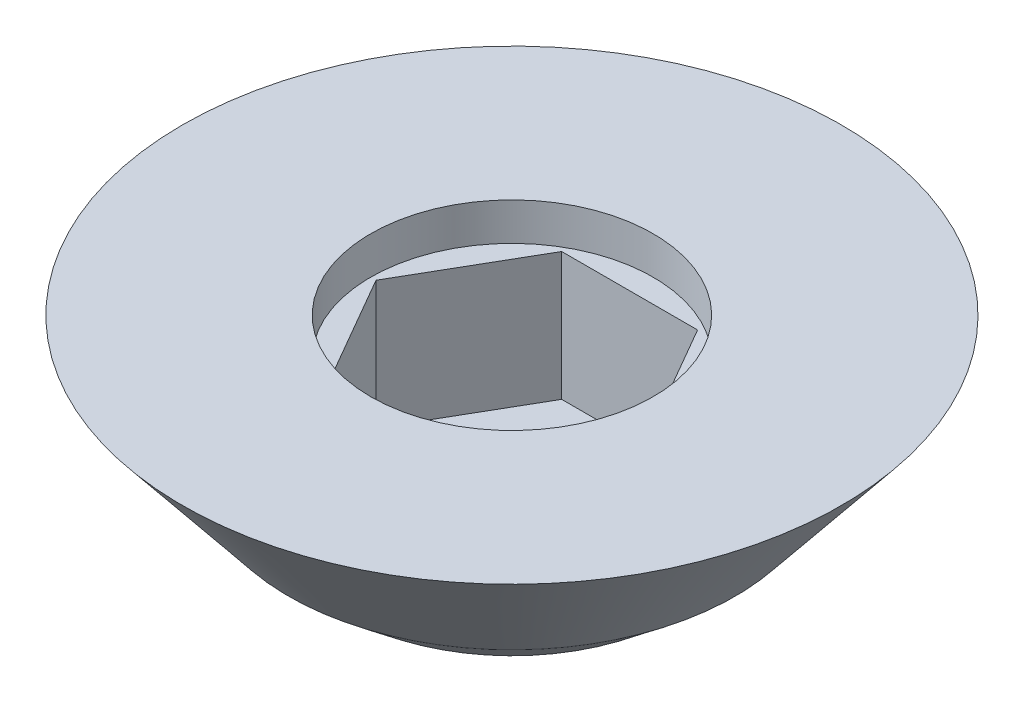
SolidWorks part; units mm, degrees
material "ABS"
ref_plane "Piano frontale" through (0, 0, 0) normal (0, 0, 1) x (1, 0, 0)
ref_plane "Piano superiore" through (0, 0, 0) normal (0, 1, 0) x (1, 0, 0)
ref_plane "Piano destro" through (0, 0, 0) normal (1, 0, 0) x (0, 0, -1)
sketch "Schizzo3" plane through (0, 0, 0) normal (0, 0, 1) x (1, 0, 0)
  line L0 (0, 0) -> (-10, 0) construction
  line L1 (-10, 0) -> (-17.5, 9.3) construction
  line L2 (-17.5, 9.3) -> (0, 9.3)
  line L3 (0, 9.3) -> (0, 0)
  line L4 (-11.8502, 2.2943) -> (-9, 0)
  line L5 (-11.8502, 2.2943) -> (-17.5, 9.3)
  line L6 (-9, 0) -> (0, 0)
  dimension "D1" = 9.3
  dimension "D2" = 10
  dimension "D3" = 17.5
  dimension "D4" = 9
  dimension "D5" = 9
revolve "Rivoluzione1" add sketch "Schizzo3" angle 360 about L3
sketch "Schizzo4" plane through (0, 9.3, 0) normal (0, 1, 0) x (1, 0, 0)
  circle A0 centre (0, 0) radius 7.5
  dimension "D1" = 15
extrude "Taglio-Estrusione1" cut sketch "Schizzo4" against normal blind 2
sketch "Schizzo5" plane through (0, 7.3, 0) normal (0, 1, 0) x (1, 0, 0)
  line L1 (3.6084, -6.25) -> (7.2169, 0)
  line L2 (7.2169, 0) -> (3.6084, 6.25)
  line L3 (3.6084, 6.25) -> (-3.6084, 6.25)
  line L4 (-3.6084, 6.25) -> (-7.2169, 0)
  line L5 (-7.2169, 0) -> (-3.6084, -6.25)
  line L6 (-3.6084, -6.25) -> (3.6084, -6.25)
  circle A0 centre (0, 0) radius 6.25 construction
  dimension "D1" = 12.5
extrude "Taglio-Estrusione2" cut sketch "Schizzo5" against normal blind 6.8
